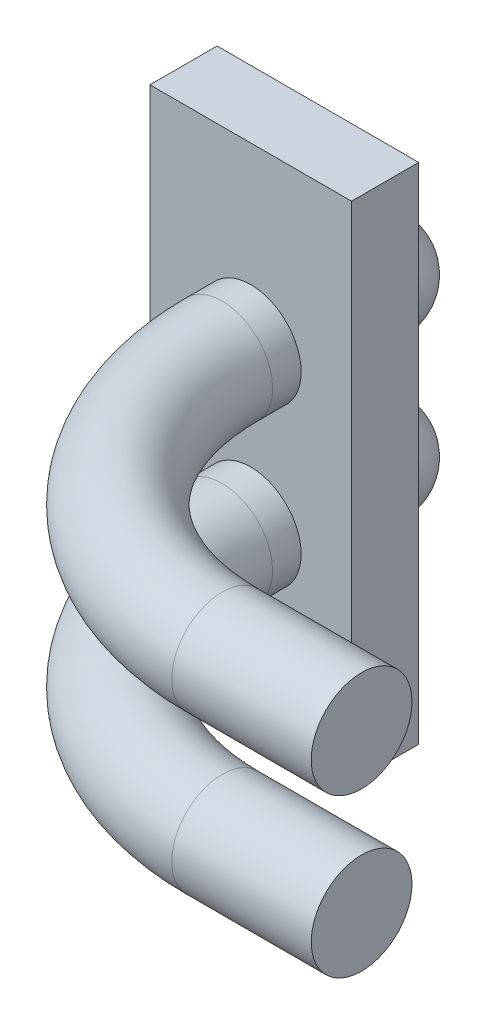
SolidWorks part; units mm, degrees
ref_plane "Front Plane" through (0, 0, 0) normal (0, 0, 1) x (1, 0, 0)
ref_plane "Top Plane" through (0, 0, 0) normal (0, 1, 0) x (1, 0, 0)
ref_plane "Right Plane" through (0, 0, 0) normal (1, 0, 0) x (0, 0, -1)
sketch "Sketch1" plane through (0, 0, 0) normal (0, 0, 1) x (1, 0, 0)
  line L1 (-3, -7.5) -> (3, -7.5)
  line L2 (-3, -7.5) -> (-3, 7.5)
  line L3 (-3, 7.5) -> (3, 7.5)
  line L4 (3, -7.5) -> (3, 7.5)
  line L5 (-3, -7.5) -> (3, 7.5) construction
  line L6 (-3, 7.5) -> (3, -7.5) construction
  point P0 (0, 0)
  dimension "D1" = 15
  dimension "D2" = 6
extrude "Boss-Extrude1" add sketch "Sketch1" along normal blind 2
sketch "Sketch2" plane through (0, 0, 0) normal (0, 0, -1) x (-1, 0, 0)
  circle A0 centre (0, 2.35) radius 1.5
  circle A1 centre (0, -2.35) radius 1.5
  dimension "D2" = 3
  dimension "D1" = 4.7
  dimension "D3" = 2.35
extrude "Boss-Extrude2" add sketch "Sketch2" along normal blind 3
fillet "Fillet1" radius 1.5 2 edges at (-1.5, -2.35, -3) (-1.5, 2.35, -3)
sketch "Sketch3" plane through (0, 0, 2) normal (0, 0, 1) x (1, 0, 0)
  circle A0 centre (0, -2.35) radius 1.5 construction
  circle A1 centre (0, 2.35) radius 1.5 construction
  circle A2 centre (0, -2.35) radius 1.5
  circle A3 centre (0, 2.35) radius 1.5
ref_plane "Plane1" through (0, 2.35, 0) normal (0, 1, 0) x (-1, 0, 0)
sketch "Sketch4" plane through (0, 2.35, 0) normal (0, 1, 0) x (-1, 0, 0)
  line L0 (0, 2) -> (0, 2.85)
  line L1 (1.5, 2) -> (-1.5, 2) construction
  line L2 (-7.5, 10.35) -> (-11.65, 10.35)
  arc A0 (0, 2.85) -> (-7.5, 10.35) centre (-7.5, 2.85) ccw
  point P8 (0, 10.35)
  dimension "D3" = 7.5
  dimension "D1" = 11.65
  dimension "D2" = 8.35
sweep "Sweep1" add profiles "Sketch3" path "Sketch4"
